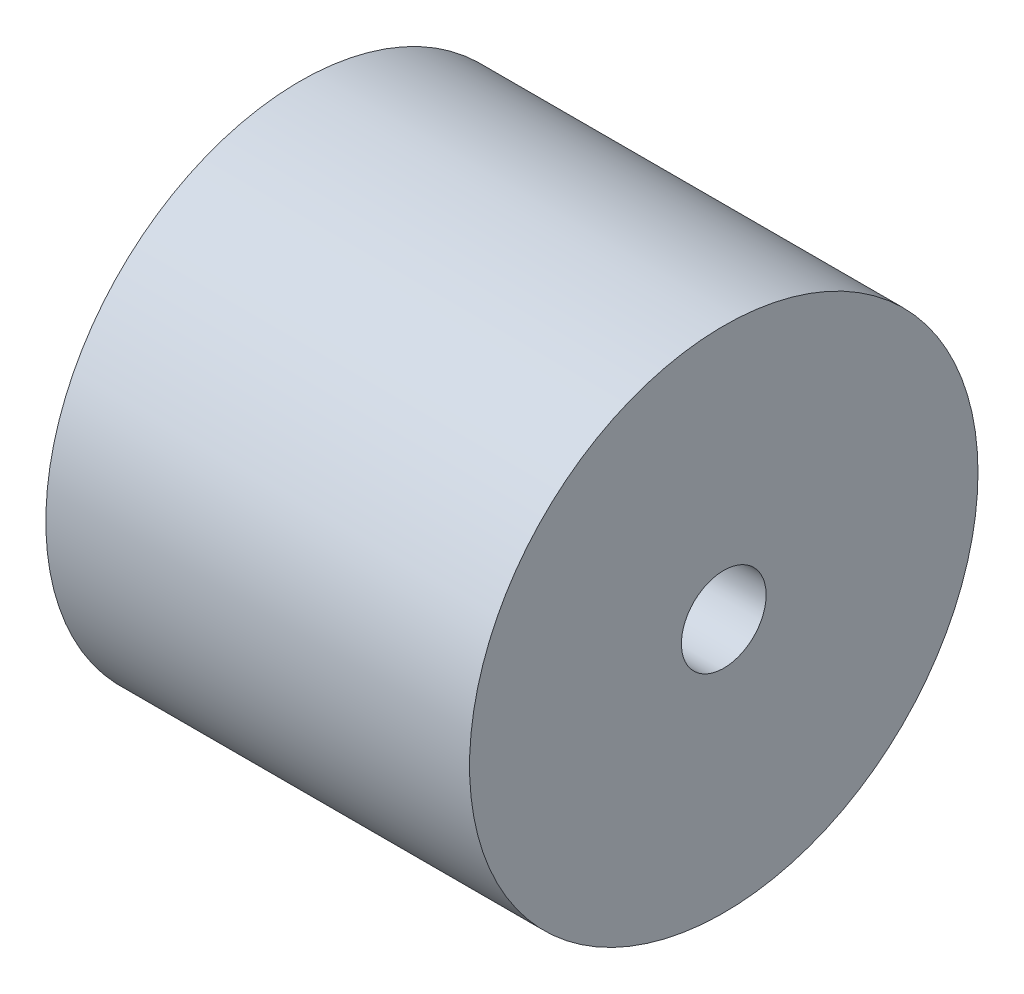
SolidWorks part; units mm, degrees
ref_plane "Piano frontale" through (0, 0, 0) normal (0, 0, 1) x (1, 0, 0)
ref_plane "Piano superiore" through (0, 0, 0) normal (0, 1, 0) x (1, 0, 0)
ref_plane "Piano destro" through (0, 0, 0) normal (1, 0, 0) x (0, 0, -1)
sketch "Schizzo1" plane through (0, 0, 0) normal (1, 0, 0) x (0, 0, -1)
  circle A0 centre (0, 0) radius 18
  dimension "D1" = 36
extrude "Estrusione-Estrusione1" add sketch "Schizzo1" along normal blind 30 contours A0
sketch "Schizzo2" plane through (0, 0, 0) normal (1, 0, 0) x (0, 0, -1)
  circle A1 centre (0, 0) radius 3
  dimension "D1" = 6
extrude "Taglio-Estrusione1" cut sketch "Schizzo2" along normal through all
